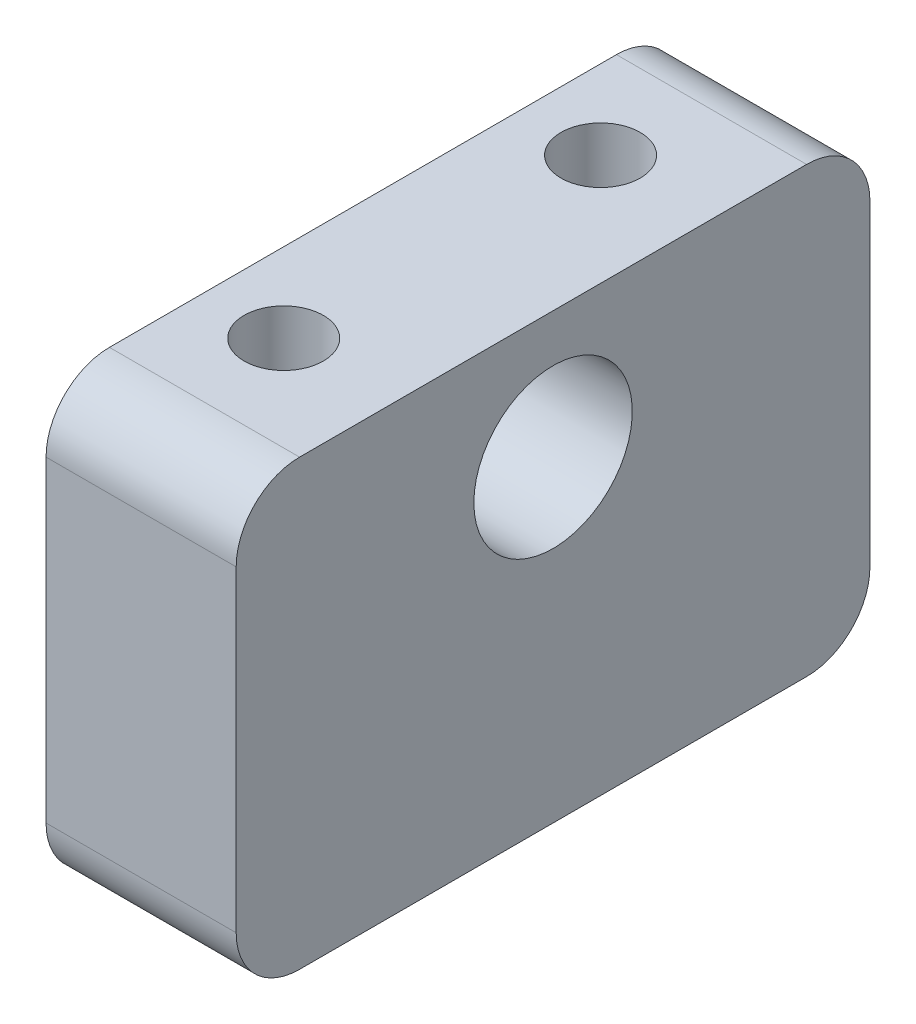
SolidWorks part; units mm, degrees
ref_plane "前视基准面" through (0, 0, 0) normal (0, 0, 1) x (1, 0, 0)
ref_plane "上视基准面" through (0, 0, 0) normal (0, 1, 0) x (1, 0, 0)
ref_plane "右视基准面" through (0, 0, 0) normal (1, 0, 0) x (0, 0, -1)
sketch "草图1" plane through (0, 0, 0) normal (0, 1, 0) x (1, 0, 0)
  line L1 (-3, -10) -> (3, -10)
  line L2 (-3, -10) -> (-3, 10)
  line L3 (-3, 10) -> (3, 10)
  line L4 (3, -10) -> (3, 10)
  line L5 (-3, -10) -> (3, 10) construction
  line L6 (-3, 10) -> (3, -10) construction
  point P0 (0, 0)
  dimension "D1" = 6
  dimension "D2" = 20
extrude "凸台-拉伸1" add sketch "草图1" along normal blind 14
sketch "草图2" plane through (0, 14, 0) normal (0, 1, 0) x (1, 0, 0)
  line L0 (3, 10) -> (-3, 10) construction
  line L2 (-3, 10) -> (-3, -10) construction
  circle A0 centre (-0.5, -5) radius 1.25
  circle A1 centre (-0.5, 5) radius 1.25
  dimension "D1" = 2.5
  dimension "D2" = 2.5
  dimension "D3" = 10
  dimension "D4" = 5
  dimension "D5" = 2.5
extrude "切除-拉伸1" cut sketch "草图2" against normal blind 14
sketch "草图3" plane through (-3, 0, 0) normal (-1, 0, 0) x (0, 0, 1)
  line L0 (-10, 14) -> (10, 14) construction
  line L1 (-10, 14) -> (-10, 0) construction
  circle A0 centre (0, 10) radius 2.5
  dimension "D1" = 5
  dimension "D2" = 4
  dimension "D3" = 10
extrude "切除-拉伸2" cut sketch "草图3" against normal blind 14
fillet "圆角1" radius 2 4 edges at (0, 0, 10) (0, 0, -10) (0, 14, 10) (0, 14, -10)
